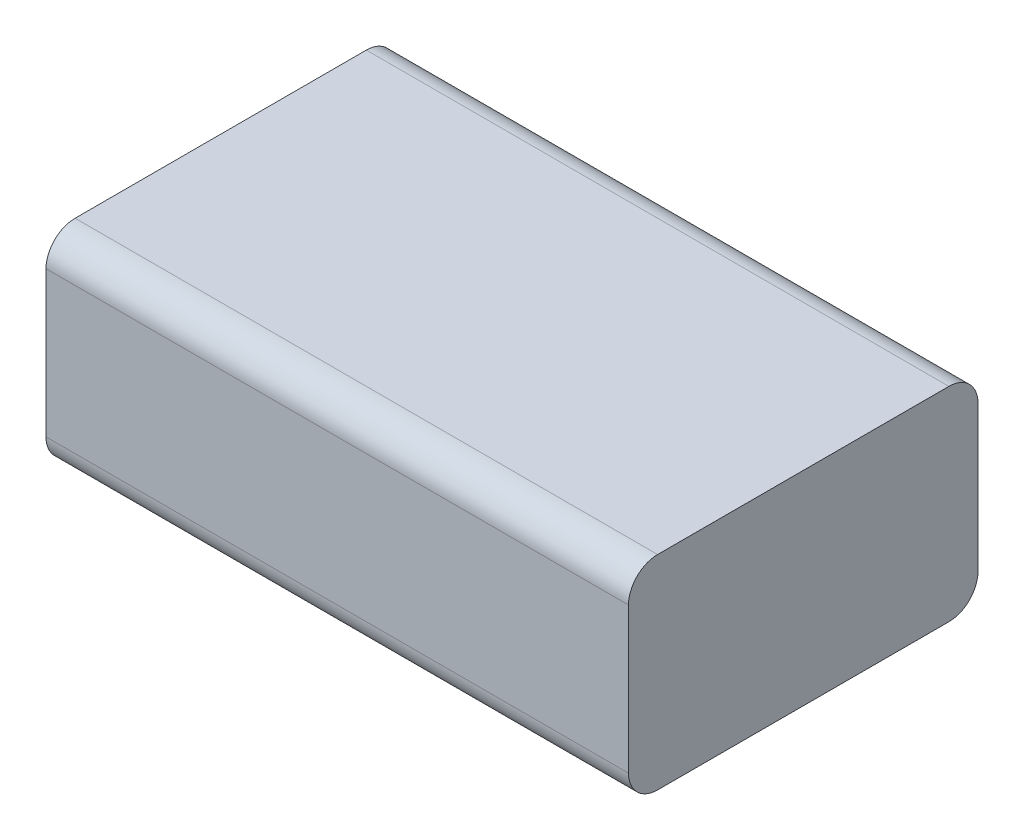
SolidWorks part; units mm, degrees
ref_plane "Front Plane" through (0, 0, 0) normal (0, 0, 1) x (1, 0, 0)
ref_plane "Top Plane" through (0, 0, 0) normal (0, 1, 0) x (1, 0, 0)
ref_plane "Right Plane" through (0, 0, 0) normal (1, 0, 0) x (0, 0, -1)
sketch "Sketch1" plane through (0, 0, 0) normal (0, 1, 0) x (1, 0, 0)
  line L2 (-50, -30) -> (50, -30)
  line L3 (-50, -30) -> (-50, 30)
  line L4 (-50, 30) -> (50, 30)
  line L5 (50, -30) -> (50, 30)
  line L6 (-50, -30) -> (50, 30) construction
  line L7 (-50, 30) -> (50, -30) construction
  point P1 (0, 0)
  dimension "D1" = 100
  dimension "D2" = 60
extrude "Boss-Extrude1" add sketch "Sketch1" along normal blind 35
fillet "Fillet1" radius 5 1 edges at (0, 35, 30)
fillet "Fillet2" radius 5 1 edges at (0, 35, -30)
fillet "Fillet3" radius 5 1 edges at (0, 0, 30)
fillet "Fillet4" radius 5 1 edges at (0, 0, -30)
sketch "Sketch2" plane through (0, 35, 0) normal (0, 1, 0) x (1, 0, 0)
  line L0 (125.4635, 400.5662) -> (721.4635, 400.5662) construction
